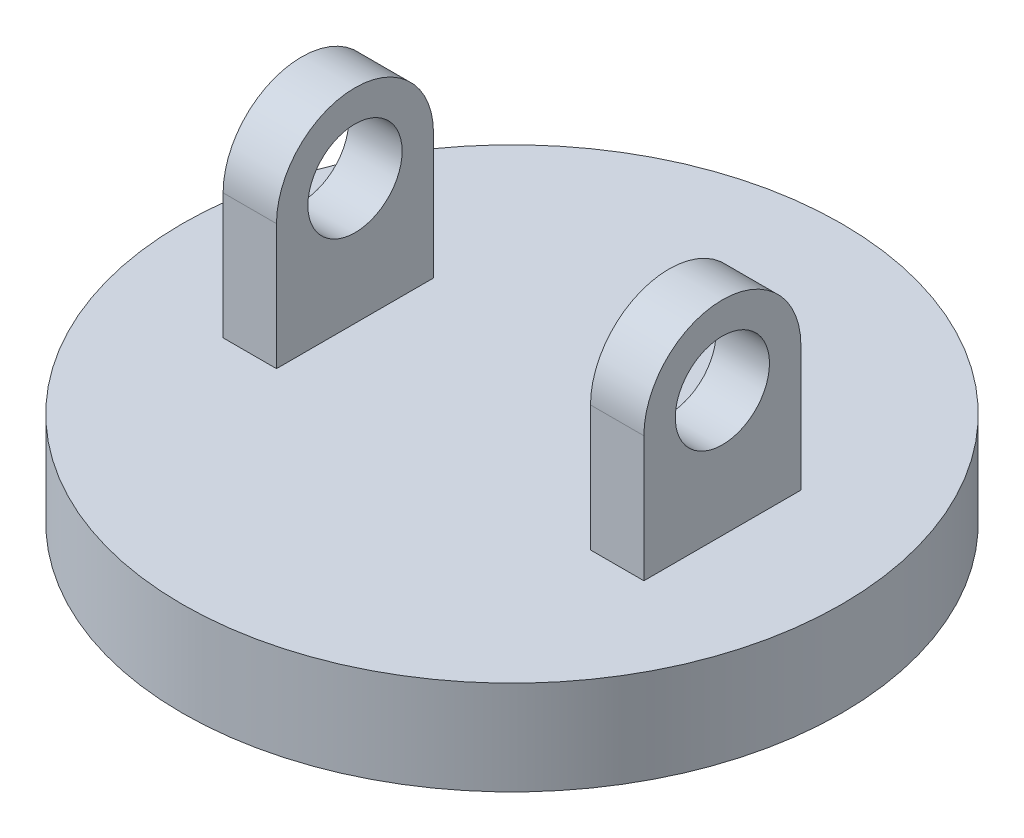
SolidWorks part; units mm, degrees
material "AISI 1020"
ref_plane "Front" through (0, 0, 0) normal (0, 0, 1) x (1, 0, 0)
ref_plane "Top" through (0, 0, 0) normal (0, 1, 0) x (1, 0, 0)
ref_plane "Right" through (0, 0, 0) normal (1, 0, 0) x (0, 0, -1)
sketch "Sketch3" plane through (0, 0, 0) normal (0, 1, 0) x (1, 0, 0)
  circle A0 centre (0, 0) radius 266.7
  dimension "D1" = 533.4
extrude "Boss-Extrude1" add sketch "Sketch3" along normal blind 76.2
sketch "Sketch4" plane through (0, 0, 0) normal (0, -1, 0) x (1, 0, 0)
  circle A0 centre (0, 0) radius 215.9
  circle A1 centre (0, 0) radius 241.3
  dimension "D1" = 431.8
  dimension "D2" = 482.6
extrude "Cut-Extrude1" cut sketch "Sketch4" against normal blind 25.4
sketch "Sketch5" plane through (0, 25.4, 0) normal (0, -1, 0) x (1, 0, 0)
  circle A0 centre (0, 0) radius 203.2
  circle A1 centre (0, 0) radius 254
  dimension "D1" = 406.4
  dimension "D2" = 50.8
extrude "Cut-Extrude2" cut sketch "Sketch5" against normal blind 25.4
sketch "Sketch6" plane through (0, 76.2, 0) normal (0, 1, 0) x (1, 0, 0)
  line L0 (-266.7, 0) -> (-148.59, 0) construction
  line L1 (-127, 0) -> (0, 0) construction
  line L2 (127, -63.5) -> (170.18, -63.5)
  line L3 (127, -63.5) -> (127, 63.5)
  line L4 (127, 63.5) -> (170.18, 63.5)
  line L5 (170.18, -63.5) -> (170.18, 63.5)
  line L6 (127, -63.5) -> (170.18, 63.5) construction
  line L7 (127, 63.5) -> (170.18, -63.5) construction
  line L8 (-170.18, -63.5) -> (-127, -63.5)
  line L9 (-170.18, -63.5) -> (-170.18, 63.5)
  line L10 (-170.18, 63.5) -> (-127, 63.5)
  line L11 (-127, -63.5) -> (-127, 63.5)
  line L12 (-170.18, -63.5) -> (-127, 63.5) construction
  line L13 (-170.18, 63.5) -> (-127, -63.5) construction
  line L14 (148.59, 0) -> (266.7, 0) construction
  line L15 (0, 0) -> (127, 0) construction
  circle A0 centre (0, 0) radius 266.7 construction
  point P0 (148.59, 0)
  point P7 (0, 0)
  point P13 (-148.59, 0)
  dimension "D2" = 43.18
  dimension "D3" = 127
  dimension "D4" = 127
  dimension "D5" = 254
extrude "Boss-Extrude2" add sketch "Sketch6" along normal blind 101.6
sketch "Sketch8" plane through (-170.18, 0, 0) normal (-1, 0, 0) x (0, 0, 1)
  line L0 (-63.5, 177.8) -> (63.5, 177.8)
  line L1 (-63.5, 177.8) -> (-63.5, 76.2) construction
  line L2 (-63.5, 177.8) -> (63.5, 177.8) construction
  arc A0 (-63.5, 177.8) -> (63.5, 177.8) centre (0, 177.8) cw
extrude "Boss-Extrude3" add sketch "Sketch8" against normal up to surface (297.18 mm away) contours A0 L0
sketch "Sketch10" plane through (170.18, 0, 0) normal (1, 0, 0) x (0, 0, -1)
  line L0 (63.5, 177.8) -> (-63.5, 177.8)
  line L1 (-63.5, 177.8) -> (63.5, 177.8) construction
  arc A0 (63.5, 177.8) -> (-63.5, 177.8) centre (0, 177.8) ccw construction
  arc A1 (63.5, 177.8) -> (-63.5, 177.8) centre (0, 177.8) ccw
extrude "Boss-Extrude4" add sketch "Sketch10" against normal up to surface (43.18 mm away) up to face at (127, 127, 0)
sketch "Sketch7" plane through (170.18, 0, 0) normal (1, 0, 0) x (0, 0, -1)
  circle A0 centre (0, 177.8) radius 38.1
  dimension "D1" = 76.2
extrude "Cut-Extrude3" cut sketch "Sketch7" against normal through all
